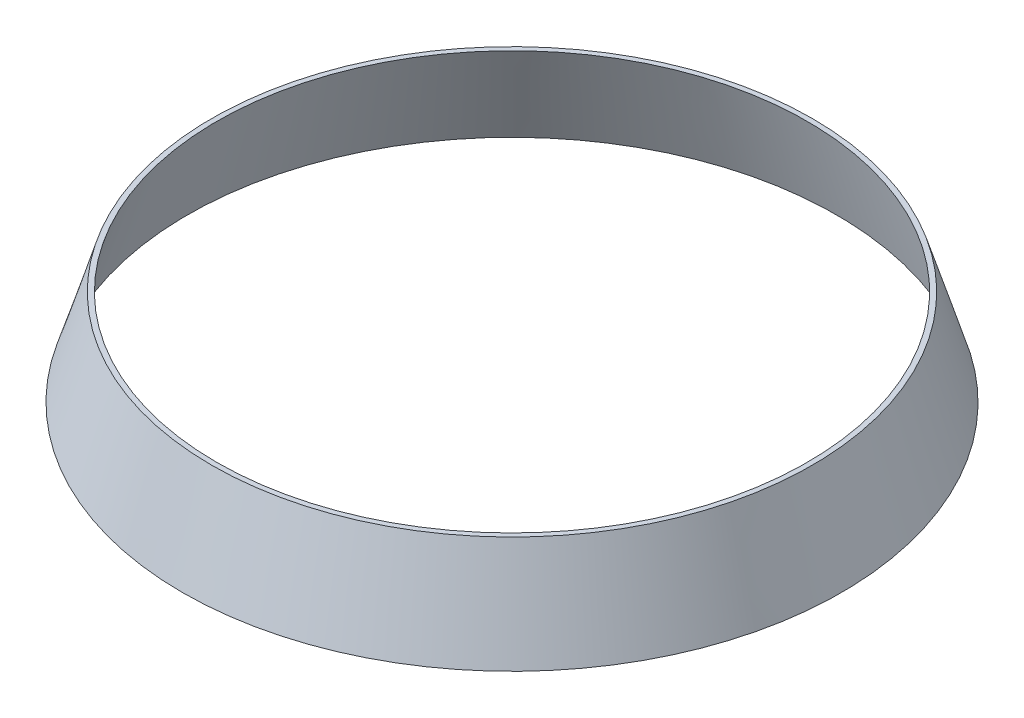
SolidWorks part; units mm, degrees
ref_plane "Front Plane" through (0, 0, 0) normal (0, 0, 1) x (1, 0, 0)
ref_plane "Top Plane" through (0, 0, 0) normal (0, 1, 0) x (1, 0, 0)
ref_plane "Right Plane" through (0, 0, 0) normal (1, 0, 0) x (0, 0, -1)
sketch "Sketch2" plane through (0, 0, 0) normal (0, 0, 1) x (1, 0, 0)
  line L0 (0, 0) -> (6.1146, 20)
  line L1 (6.1146, 20) -> (67.8646, 20)
  line L2 (0, 0) -> (67.8646, 0)
  line L3 (67.8646, 20) -> (67.8646, 0)
  dimension "D1" = 61.75
revolve "Revolve1" add sketch "Sketch2" angle 360 about L3
shell "Shell1" thickness 1
